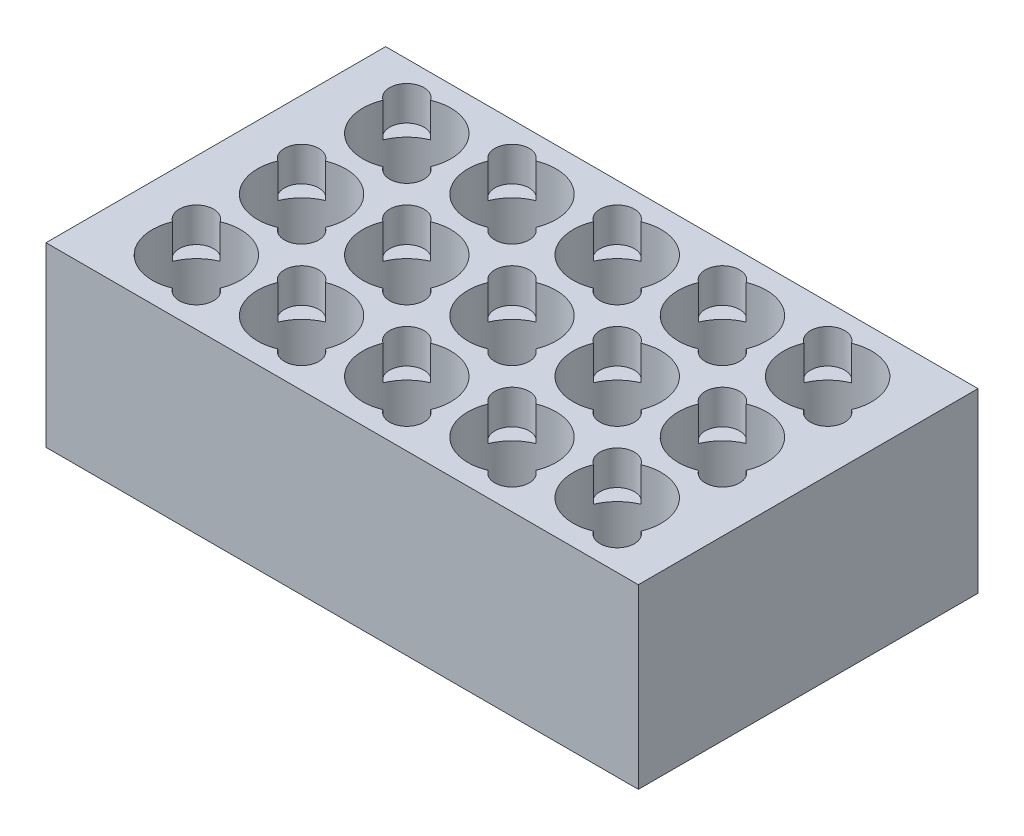
SolidWorks part; units mm, degrees
ref_plane "Спереди" through (0, 0, 0) normal (0, 0, 1) x (1, 0, 0)
ref_plane "Сверху" through (0, 0, 0) normal (0, 1, 0) x (1, 0, 0)
ref_plane "Справа" through (0, 0, 0) normal (1, 0, 0) x (0, 0, -1)
sketch "Матрица 5*3" plane through (0, 0, 0) normal (0, 1, 0) x (1, 0, 0)
  circle A0 centre (0, 0) radius 38.5
  circle A1 centre (92, 0) radius 38.5
  circle A2 centre (184, 0) radius 38.5
  circle A3 centre (276, 0) radius 38.5
  circle A4 centre (368, 0) radius 38.5
  circle A5 centre (0, -92) radius 38.5
  circle A6 centre (92, -92) radius 38.5
  circle A7 centre (184, -92) radius 38.5
  circle A8 centre (276, -92) radius 38.5
  circle A9 centre (368, -92) radius 38.5
  circle A10 centre (0, -184) radius 38.5
  circle A11 centre (92, -184) radius 38.5
  circle A12 centre (184, -184) radius 38.5
  circle A13 centre (276, -184) radius 38.5
  circle A14 centre (368, -184) radius 38.5
  dimension "D1" = 77
  dimension "D3" = 15
  dimension "D5" = 15
  dimension "D6" = 368
  dimension "D7" = 184
  dimension "D2" = 5
  dimension "D4" = 3
sketch "Габариты" plane through (0, 0, 0) normal (0, 1, 0) x (1, 0, 0)
  line L0 (443, 56.5) -> (-75, -240.5) construction
  line L1 (-75, 56.5) -> (443, 56.5)
  line L2 (-75, 56.5) -> (-75, -240.5)
  line L3 (-75, -240.5) -> (443, -240.5)
  line L4 (443, 56.5) -> (443, -240.5)
  line L5 (-75, 56.5) -> (443, -240.5) construction
  point P4 (184, -92)
  dimension "D1" = 297
  dimension "D2" = 518
extrude "Нижний наполнитель" add sketch "Габариты" against normal blind 155
extrude "Ложемент для КМЕ-11" cut sketch "Матрица 5*3" against normal blind 123
sketch "Эскиз1" plane through (0, 0, 0) normal (0, 1, 0) x (1, 0, 0)
  line L0 (0, 0) -> (184, -184) construction
  line L1 (-27.2236, -27.2236) -> (27.2236, 27.2236) construction
  circle A0 centre (27.2236, -27.2236) radius 15
  circle A1 centre (0, 0) radius 38.5 construction
  circle A2 centre (-27.2236, 27.2236) radius 15
  circle A3 centre (119.2236, -27.2236) radius 15
  circle A4 centre (64.7764, 27.2236) radius 15
  circle A5 centre (211.2236, -27.2236) radius 15
  circle A6 centre (156.7764, 27.2236) radius 15
  circle A7 centre (303.2236, -27.2236) radius 15
  circle A8 centre (248.7764, 27.2236) radius 15
  circle A9 centre (395.2236, -27.2236) radius 15
  circle A10 centre (340.7764, 27.2236) radius 15
  circle A11 centre (119.2236, -119.2236) radius 15
  circle A12 centre (64.7764, -64.7764) radius 15
  circle A13 centre (211.2236, -119.2236) radius 15
  circle A14 centre (156.7764, -64.7764) radius 15
  circle A15 centre (303.2236, -119.2236) radius 15
  circle A16 centre (248.7764, -64.7764) radius 15
  circle A17 centre (395.2236, -119.2236) radius 15
  circle A18 centre (340.7764, -64.7764) radius 15
  circle A19 centre (119.2236, -211.2236) radius 15
  circle A20 centre (64.7764, -156.7764) radius 15
  circle A21 centre (211.2236, -211.2236) radius 15
  circle A22 centre (156.7764, -156.7764) radius 15
  circle A23 centre (303.2236, -211.2236) radius 15
  circle A24 centre (248.7764, -156.7764) radius 15
  circle A25 centre (395.2236, -211.2236) radius 15
  circle A26 centre (340.7764, -156.7764) radius 15
  circle A27 centre (27.2236, -119.2236) radius 15
  circle A28 centre (-27.2236, -64.7764) radius 15
  circle A29 centre (27.2236, -211.2236) radius 15
  circle A30 centre (-27.2236, -156.7764) radius 15
  circle A31 centre (92, 0) radius 38.5 construction
  circle A32 centre (0, -92) radius 38.5 construction
  circle A33 centre (0, 0) radius 38.5 construction
  circle A34 centre (92, 0) radius 38.5 construction
  circle A35 centre (0, -92) radius 38.5 construction
  dimension "D1" = 30
  dimension "D2" = 3
  dimension "D3" = 5
extrude "Хват" cut sketch "Эскиз1" against normal blind 30
